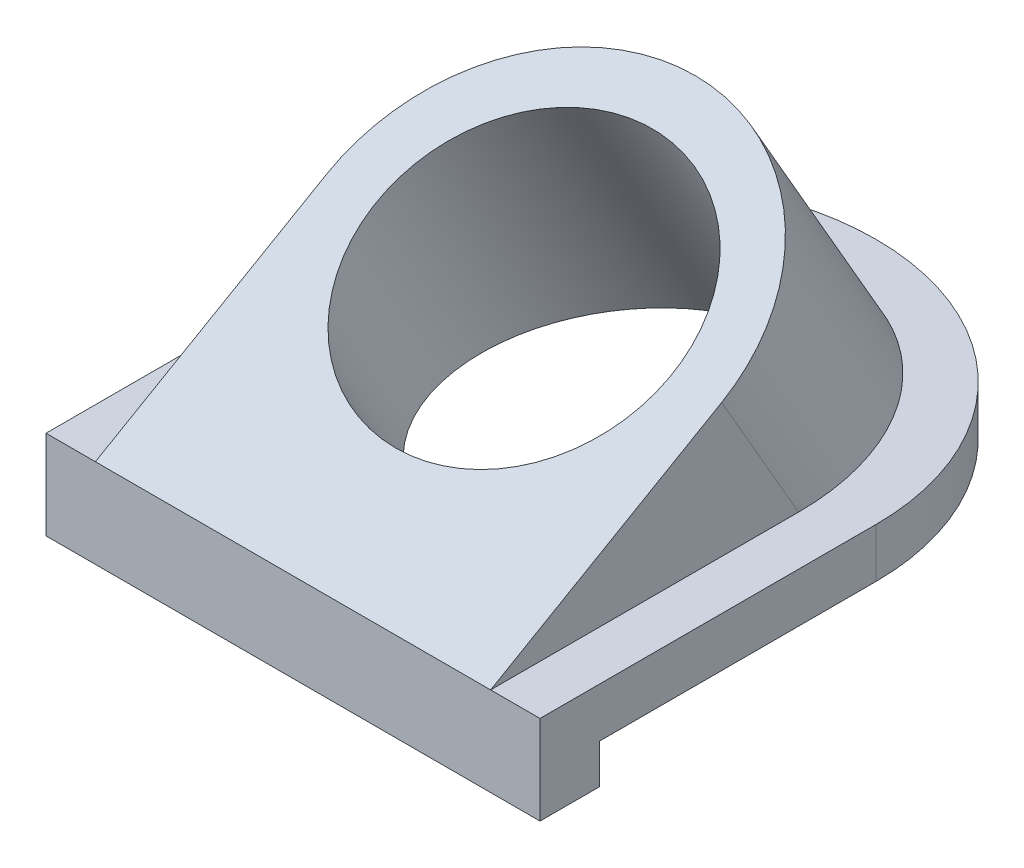
SolidWorks part; units mm, degrees
ref_plane "前基準面" through (0, 0, 0) normal (0, 0, 1) x (1, 0, 0)
ref_plane "上基準面" through (0, 0, 0) normal (0, 1, 0) x (1, 0, 0)
ref_plane "右基準面" through (0, 0, 0) normal (1, 0, 0) x (0, 0, -1)
sketch "草圖7" plane through (0, 0, 0) normal (0, 1, 0) x (1, 0, 0)
  line L0 (-50, 0) -> (50, 0)
  line L1 (50, 0) -> (50, 68)
  line L2 (-50, 0) -> (-50, 68)
  arc A0 (50, 68) -> (-50, 68) centre (0, 68) ccw
  point P7 (0, 0)
  dimension "D1" = 100
  dimension "D2" = 68
extrude "填料-伸長3" add sketch "草圖7" against normal blind 18
sketch "草圖8" plane through (0, -18, 0) normal (0, -1, 0) x (1, 0, 0)
  line L0 (-50, -68) -> (-50, 0) construction
  line L1 (-50, -12) -> (50, -12)
  line L2 (-50, -12) -> (-50, -118)
  line L3 (-50, -118) -> (50, -118)
  line L4 (50, -12) -> (50, -118)
  line L5 (50, 0) -> (50, -68) construction
  line L6 (-50, 0) -> (50, 0) construction
  arc A0 (-50, -68) -> (50, -68) centre (0, -68) ccw construction
  point P6 (0, 0)
  point P7 (0, 0)
  point P10 (0, -118)
  dimension "D1" = 12
extrude "除料-伸長1" cut sketch "草圖8" against normal blind 8
sketch "草圖15" plane through (0, 0, 0) normal (1, 0, 0) x (0, 0, -1)
  line L0 (68, 0) -> (51, 29.4449) construction
  line L1 (0, 0) -> (68, 0) construction
  dimension "D1" = 60
  dimension "D2" = 34
ref_plane "平面3" through (0, 29.4449, -51) normal (0, 0.866, 0.5) x (1, 0, 0)
sketch "草圖16" plane through (0, 29.4449, -51) normal (0, 0.866, 0.5) x (1, 0, 0)
  line L0 (-40, -58.8897) -> (40, -58.8897)
  line L1 (40, -58.8897) -> (40, -4.8897)
  line L2 (-40, -4.8897) -> (-40, -58.8897)
  arc A0 (40, -4.8897) -> (-40, -4.8897) centre (0, -4.8897) ccw
  point P6 (0, 0)
  point P7 (0, -4.8897)
  point P8 (0, -4.8897)
  dimension "D1" = 40
  dimension "D2" = 54
extrude "填料-伸長5" add sketch "草圖16" against normal up to surface (42.7239 mm away)
sketch "草圖18" plane through (0, 29.4449, -51) normal (0, 0.866, 0.5) x (1, 0, 0)
  line L0 (-40, -58.8897) -> (40, -58.8897) construction
  circle A0 centre (0, -4.8897) radius 30
  dimension "D1" = 60
  dimension "D2" = 40
  dimension "D3" = 54
extrude "除料-伸長2" cut sketch "草圖18" against normal up to surface (25.4034 mm away)
